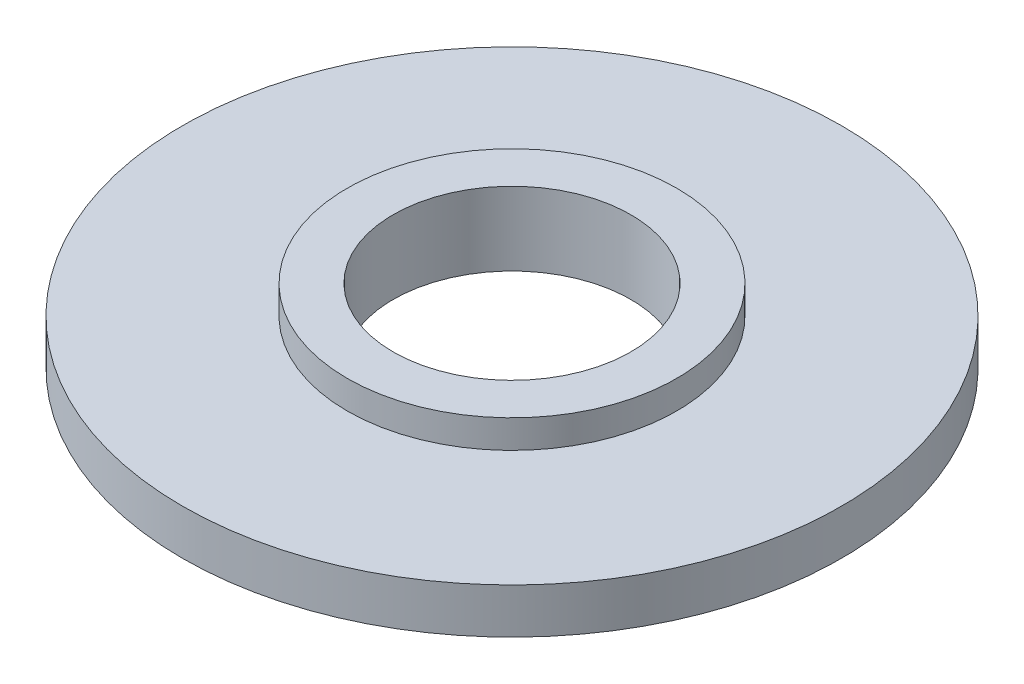
SolidWorks part; units mm, degrees
ref_plane "Alzado" through (0, 0, 0) normal (0, 0, 1) x (1, 0, 0)
ref_plane "Planta" through (0, 0, 0) normal (0, 1, 0) x (1, 0, 0)
ref_plane "Vista lateral" through (0, 0, 0) normal (1, 0, 0) x (0, 0, -1)
sketch "Sketch1" plane through (0, 0, 0) normal (0, 1, 0) x (1, 0, 0)
  circle A0 centre (0, 0) radius 5.05
  circle A1 centre (0, 0) radius 14
  dimension "D1" = 10.1
  dimension "D2" = 28
extrude "Boss-Extrude1" add sketch "Sketch1" along normal blind 1.92
sketch "Sketch2" plane through (0, 1.92, 0) normal (0, 1, 0) x (1, 0, 0)
  circle A0 centre (0, 0) radius 5.05
  circle A1 centre (0, 0) radius 7
  circle A2 centre (0, 0) radius 5.05 construction
  dimension "D1" = 14
extrude "Boss-Extrude2" add sketch "Sketch2" along normal blind 1.2
